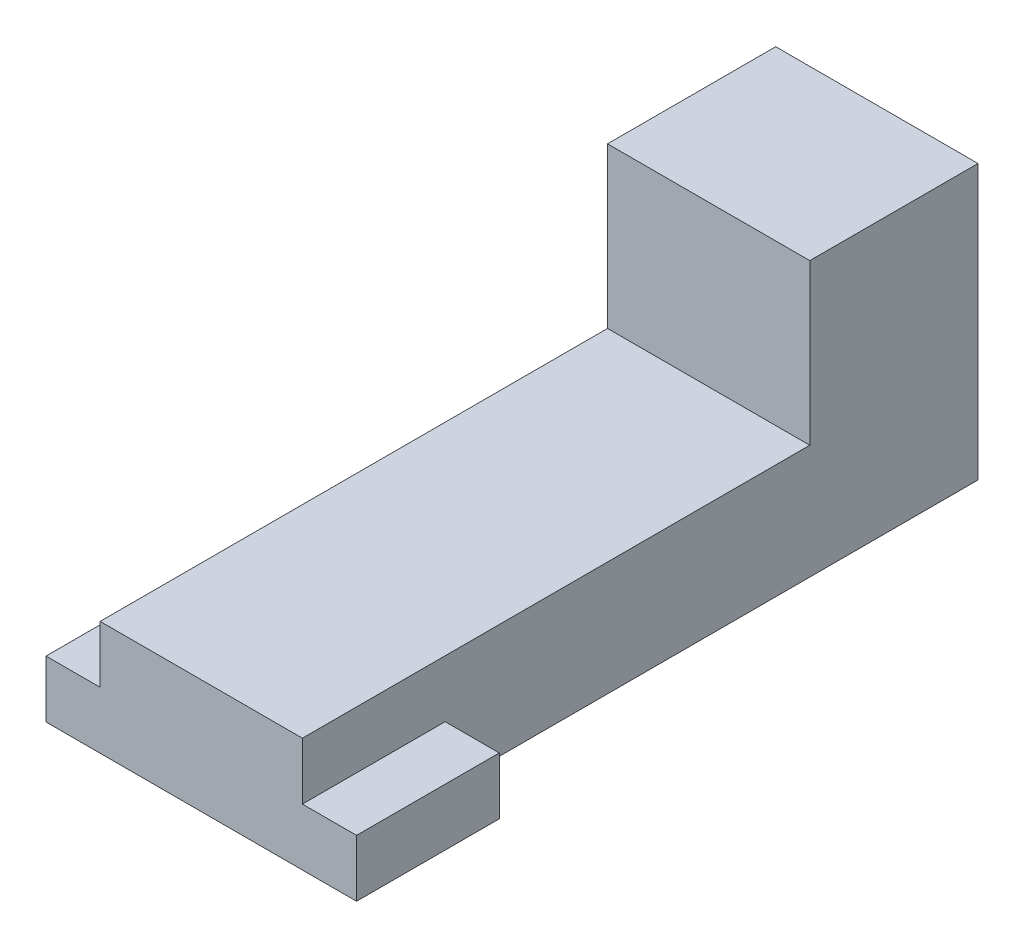
SolidWorks part; units mm, degrees
ref_plane "Front Plane" through (0, 0, 0) normal (0, 0, 1) x (1, 0, 0)
ref_plane "Top Plane" through (0, 0, 0) normal (0, 1, 0) x (1, 0, 0)
ref_plane "Right Plane" through (0, 0, 0) normal (1, 0, 0) x (0, 0, -1)
sketch "Sketch1" plane through (0, 0, 0) normal (0, 0, 1) x (1, 0, 0)
  line L1 (-679.795, 125) -> (679.795, 125)
  line L2 (-679.795, 125) -> (-679.795, -125)
  line L3 (-679.795, -125) -> (679.795, -125)
  line L4 (679.795, 125) -> (679.795, -125)
  line L5 (-679.795, 125) -> (679.795, -125) construction
  line L6 (-679.795, -125) -> (679.795, 125) construction
  point P0 (0, 0)
  dimension "D1" = 250
  dimension "D2" = 1359.59
extrude "Boss-Extrude1" add sketch "Sketch1" along normal blind 625
sketch "Sketch2" plane through (0, 0, 625) normal (0, 0, 1) x (1, 0, 0)
  line L0 (0, 0) -> (0, 293.2655) construction
  line L1 (-679.795, -125) -> (679.795, -125) construction
  line L2 (442.8, 375) -> (-442.8, 375)
  line L3 (442.8, 375) -> (442.8, -125)
  line L4 (442.8, -125) -> (-442.8, -125)
  line L5 (-442.8, 375) -> (-442.8, -125)
  line L6 (442.8, 375) -> (-442.8, -125) construction
  line L7 (442.8, -125) -> (-442.8, 375) construction
  point P3 (0, 125)
  dimension "D1" = 500
  dimension "D2" = 885.6
extrude "Boss-Extrude2" add sketch "Sketch2" against normal up to surface (2957.87 mm away)
sketch "Sketch3" plane through (0, 375, 0) normal (0, 1, 0) x (1, 0, 0)
  line L1 (-442.8, 2332.87) -> (442.8, 2332.87)
  line L2 (-442.8, 2332.87) -> (-442.8, 1596.39)
  line L3 (-442.8, 1596.39) -> (442.8, 1596.39)
  line L4 (442.8, -625) -> (442.8, 2332.87)
  line L5 (442.8, 2332.87) -> (-442.8, 2332.87)
  line L6 (-442.8, 2332.87) -> (-442.8, -625)
  line L7 (-442.8, -625) -> (442.8, -625)
  line L8 (442.8, -625) -> (442.8, 2332.87) construction
  line L9 (442.8, 2332.87) -> (-442.8, 2332.87) construction
  line L10 (-442.8, 2332.87) -> (-442.8, -625) construction
  line L11 (-442.8, -625) -> (442.8, -625) construction
  line L12 (442.8, 2332.87) -> (442.8, 1596.39)
  arc A0 (496.915, 1675.2) -> (649.315, 1675.2) centre (573.115, 2435.295) ccw construction
  arc A1 (496.915, 1675.2) -> (649.315, 1675.2) centre (573.115, 2435.295) ccw construction
  point P9 (573.115, 1671.39)
  dimension "D2" = 75
  dimension "D1" = 0
extrude "Boss-Extrude4" add sketch "Sketch3" along normal blind 700
